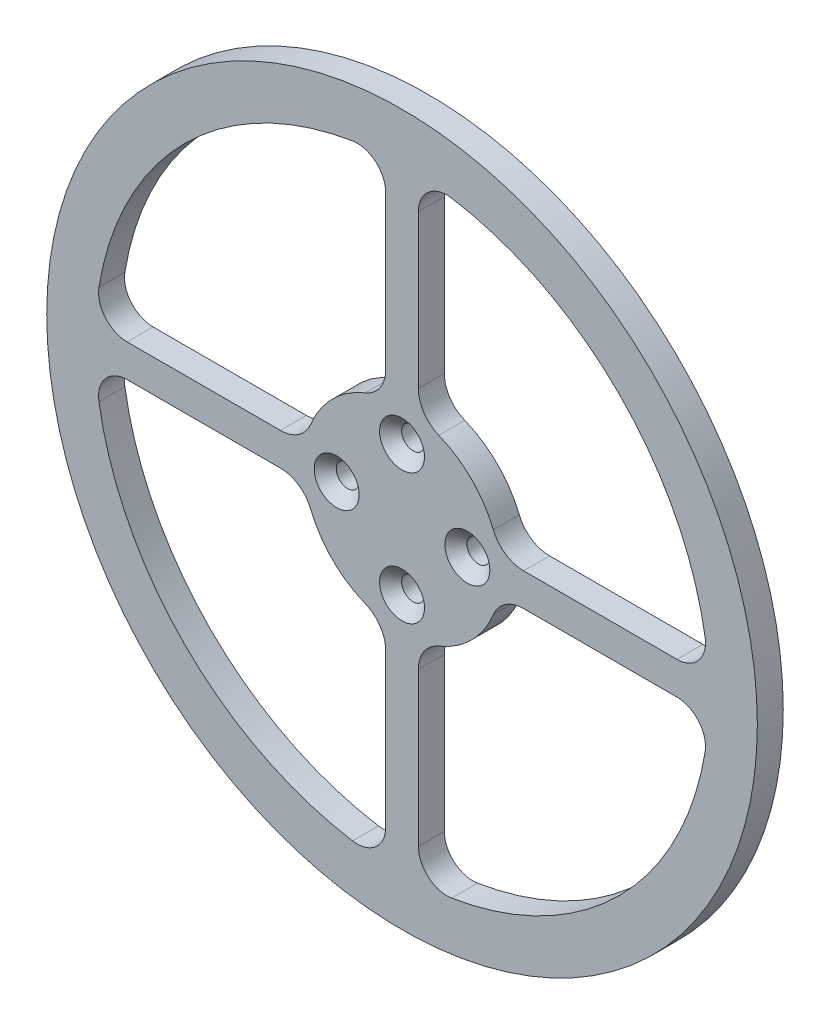
SolidWorks part; units mm, degrees
material "PETG_SRD"
ref_plane "Front Plane" through (0, 0, 0) normal (0, 0, 1) x (1, 0, 0)
ref_plane "Top Plane" through (0, 0, 0) normal (0, 1, 0) x (1, 0, 0)
ref_plane "Right Plane" through (0, 0, 0) normal (1, 0, 0) x (0, 0, -1)
sketch "Sketch1" plane through (0, 0, 0) normal (0, 0, 1) x (1, 0, 0)
  line L0 (0, 37.6) -> (0, -37.4) construction
  line L1 (-37.4, 0) -> (37.6, 0) construction
  line L2 (-37.5468, -2) -> (-11.8829, -2)
  line L3 (-2, 37.5468) -> (-2, 11.8829)
  line L4 (-37.5468, 2) -> (-11.8829, 2)
  line L5 (2, 37.5468) -> (2, 11.8829)
  line L6 (-37.4, 2) -> (37.6, 2) construction
  line L7 (-37.4, -2) -> (37.6, -2) construction
  line L8 (-2, 37.6) -> (-2, -37.4) construction
  line L9 (2, 37.6) -> (2, -37.4) construction
  line L10 (-2, -11.8829) -> (-2, -37.5468)
  line L11 (11.8829, -2) -> (37.5468, -2)
  line L12 (2, -11.8829) -> (2, -37.5468)
  line L13 (11.8829, 2) -> (37.5468, 2)
  circle A0 centre (0, 0) radius 43.5
  circle A1 centre (0, 8) radius 1.4
  circle A2 centre (0, -8) radius 1.4
  circle A3 centre (8, 0) radius 1.4
  circle A4 centre (-8, 0) radius 1.4
  circle A5 centre (0, 0) radius 8 construction
  arc A23 (-37.5468, -2) -> (-2, -37.5468) centre (0, 0) ccw
  arc A24 (2, -37.5468) -> (37.5468, -2) centre (0, 0) ccw
  arc A25 (37.5468, 2) -> (2, 37.5468) centre (0, 0) ccw
  arc A26 (-2, 37.5468) -> (-37.5468, 2) centre (0, 0) ccw
  arc A27 (-11.8829, -2) -> (-2, -11.8829) centre (0, 0) ccw
  arc A28 (-2, 11.8829) -> (-11.8829, 2) centre (0, 0) ccw
  arc A29 (11.8829, 2) -> (2, 11.8829) centre (0, 0) ccw
  arc A30 (2, -11.8829) -> (11.8829, -2) centre (0, 0) ccw
  dimension "D1" = 2.8
  dimension "D2" = 16
  dimension "D3" = 87
  dimension "D4" = 5.9
  dimension "D7" = 4.05
  dimension "D5" = 2
  dimension "D6" = 2
extrude "Boss-Extrude1" add sketch "Sketch1" along normal blind 3.175
ref_plane "Plane5" through (0, 0, -3.175) normal (0, 0, 1) x (1, 0, 0)
fillet "Fillet1" radius 4 8 edges at (2, 11.8829, 1.5875) (11.8829, 2, 1.5875) (11.8829, -2, 1.5875) (2, -11.8829, 1.5875) (-2, -11.8829, 1.5875) (-11.8829, 2, 1.5875) (-2, 11.8829, 1.5875) (-11.8829, -2, 1.5875)
fillet "Fillet2" radius 3.5 8 edges at (2, -37.5468, 1.5875) (-2, -37.5468, 1.5875) (37.5468, -2, 1.5875) (37.5468, 2, 1.5875) (2, 37.5468, 1.5875) (-2, 37.5468, 1.5875) (-37.5468, 2, 1.5875) (-37.5468, -2, 1.5875)
sketch "Sketch3" plane through (0, 0, 0) normal (0, 0, -1) x (-1, 0, 0)
  circle A0 centre (0, 0) radius 3.15
  dimension "D1" = 6.3
extrude "Boss-Extrude2" add sketch "Sketch3" along normal up to surface (3.175 mm away) up to plane "Plane5"
chamfer "Chamfer1" distance 1.35 angle 45 4 edges at (-6.6, 0, 3.175) (1.4, -8, 3.175) (9.4, 0, 3.175) (1.4, 8, 3.175)
equation "\"Rim\"= 5.9"
equation "\"D4@Sketch1\"=\"Rim\""
equation "\"`.14\"=1.5"
